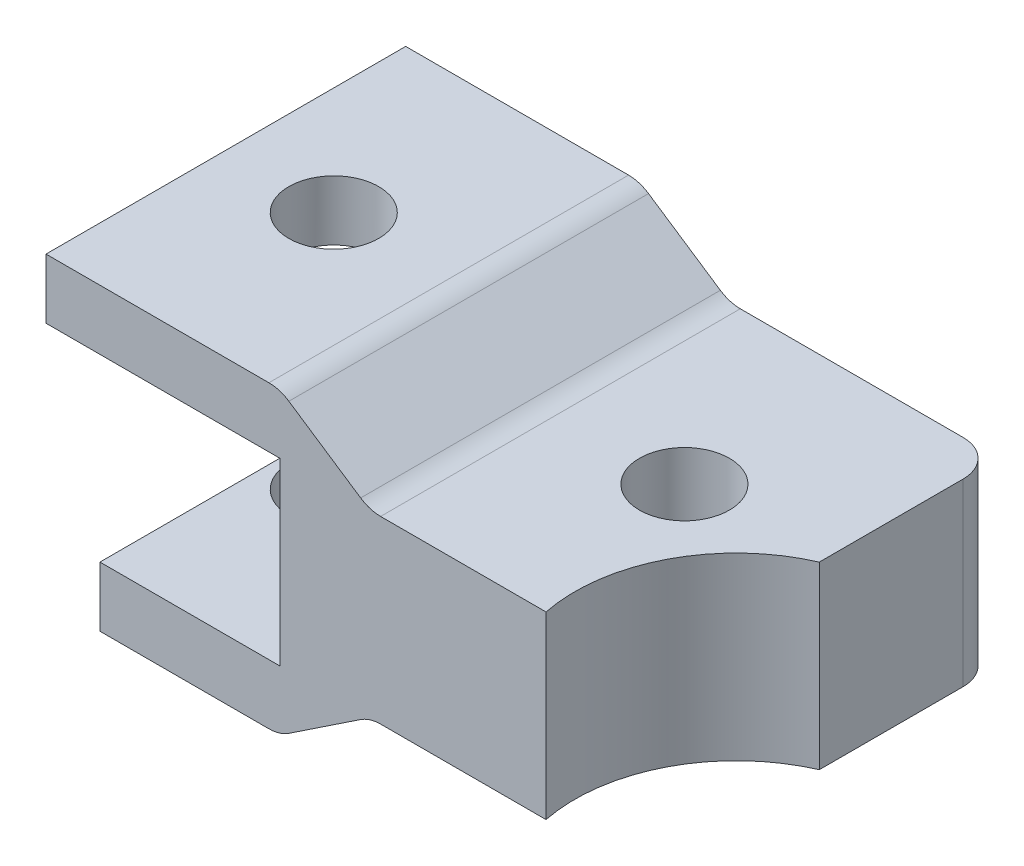
SolidWorks part; units mm, degrees
ref_plane "Front Plane" through (0, 0, 0) normal (0, 0, 1) x (1, 0, 0)
ref_plane "Top Plane" through (0, 0, 0) normal (0, 1, 0) x (1, 0, 0)
ref_plane "Right Plane" through (0, 0, 0) normal (1, 0, 0) x (0, 0, -1)
sketch "Sketch1" plane through (0, 0, 0) normal (0, 0, 1) x (1, 0, 0)
  line L0 (38.1, 0) -> (38.1, 12.7)
  line L1 (0, 0) -> (12.7, 0)
  line L2 (0, 0) -> (0, -4.2316)
  line L3 (0, -4.2316) -> (12.7, -4.2316)
  line L4 (12.7, 0) -> (12.7, -4.2316)
  line L5 (6.35, -4.2316) -> (6.35, 0) construction
  line L6 (0, -2.1158) -> (12.7, -2.1158) construction
  line L8 (12.7, -4.2316) -> (12.7, 16.9316)
  line L12 (12.7, 6.35) -> (38.1, 6.35) construction
  line L13 (12.7, 16.9316) -> (-3.81, 16.9316)
  line L14 (12.7, 16.9316) -> (12.7, 12.7)
  line L15 (12.7, 12.7) -> (-3.81, 12.7)
  line L16 (-3.81, 16.9316) -> (-3.81, 12.7)
  line L17 (4.445, 12.7) -> (4.445, 16.9316) construction
  line L18 (12.7, 14.8158) -> (-3.81, 14.8158) construction
  line L20 (12.7, -4.2316) -> (19.05, 0)
  line L21 (12.7, 16.9316) -> (19.05, 12.7)
  line L22 (19.05, 0) -> (38.1, 0)
  line L23 (19.05, 12.7) -> (38.1, 12.7)
  point P220 (6.35, -2.1158)
  point P325 (25.4, 6.35)
  point P337 (4.445, 14.8158)
  dimension "D1" = 4.2316
  dimension "D2" = 12.7
  dimension "D3" = 12.7
  dimension "D4" = 25.4
  dimension "D5" = 16.51
  dimension "D6" = 6.35
  dimension "D7" = 6.35
  dimension "D8" = 12.7
extrude "Boss-Extrude1" add sketch "Sketch1" along normal blind 25.4
sketch "Sketch4" plane through (0, 0, 0) normal (0, 1, 0) x (1, 0, 0)
  circle A0 centre (3.81, -12.7) radius 3.175
extrude "Cut-Extrude4" cut sketch "Sketch4" against normal through all both and the other way through all
sketch "Sketch6" plane through (0, 12.7, 0) normal (0, 1, 0) x (1, 0, 0)
  line L0 (38.1, -12.7) -> (19.05, -12.7) construction
  line L1 (38.1, -25.4) -> (38.1, 0) construction
  line L2 (19.05, -25.4) -> (19.05, 0) construction
  circle A0 centre (28.575, -12.7) radius 3.175
  dimension "D1" = 6.35
extrude "Cut-Extrude5" cut sketch "Sketch6" against normal through all both and the other way through all
sketch "Sketch7" plane through (0, 12.7, 0) normal (0, 1, 0) x (1, 0, 0)
  line L0 (31.5003, -93) -> (31.5003, -25.4) construction
  line L1 (19.05, -25.4) -> (38.1, -25.4) construction
  line L2 (31.9773, -100.8185) -> (31.9773, -19.1999) construction
  line L3 (37.4184, -19.1997) -> (28.5752, -19.2) construction
  line L4 (38.1, -25.4) -> (38.1, 0) construction
  line L5 (38.1, -12.7) -> (38.1, -25.4)
  line L6 (38.1, -25.4) -> (31.5003, -25.4)
  arc A0 (31.5003, -93) -> (38.1033, -105.7) centre (40.5275, -96.373) ccw construction
  arc A1 (31.5003, -25.4) -> (38.1, -12.7) centre (42.6728, -23.1412) cw
extrude "Cut-Extrude6" cut sketch "Sketch7" against normal through all both and the other way through all
fillet "Fillet2" radius 2.54 5 edges at (38.1, 6.35, 0) (19.05, 0, 12.7) (19.05, 12.7, 12.7) (12.7, 16.9316, 12.7) (12.7, -4.2316, 12.7)
